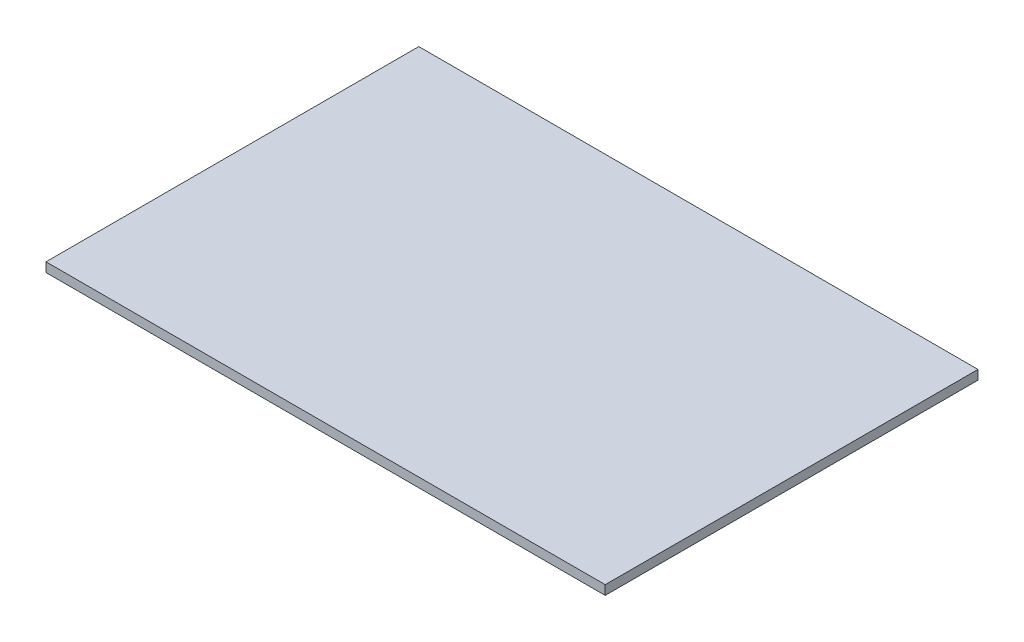
SolidWorks part; units mm, degrees
material "Alloy Steel"
ref_plane "Front Plane" through (0, 0, 0) normal (0, 0, 1) x (1, 0, 0)
ref_plane "Top Plane" through (0, 0, 0) normal (0, 1, 0) x (1, 0, 0)
ref_plane "Right Plane" through (0, 0, 0) normal (1, 0, 0) x (0, 0, -1)
sketch "Sketch1" plane through (0, 0, 0) normal (0, 1, 0) x (1, 0, 0)
  line L1 (-1500, 1000) -> (1500, 1000)
  line L2 (-1500, 1000) -> (-1500, -1000)
  line L3 (-1500, -1000) -> (1500, -1000)
  line L4 (1500, 1000) -> (1500, -1000)
  line L5 (-1500, 1000) -> (1500, -1000) construction
  line L6 (-1500, -1000) -> (1500, 1000) construction
  point P0 (0, 0)
  dimension "D1" = 2000
  dimension "D2" = 3000
extrude "Boss-Extrude1" add sketch "Sketch1" along normal blind 50
